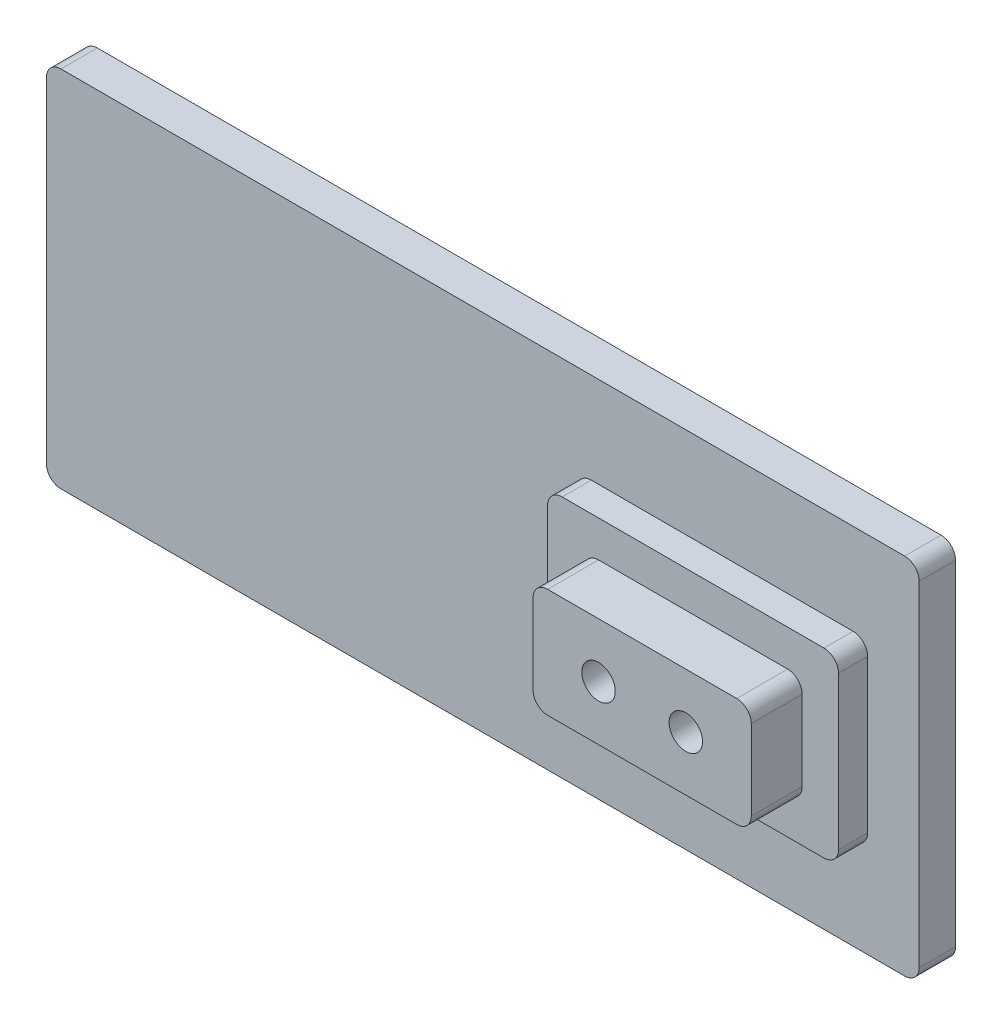
SolidWorks part; units mm, degrees
material "ABS"
ref_plane "Alzado" through (0, 0, 0) normal (0, 0, 1) x (1, 0, 0)
ref_plane "Planta" through (0, 0, 0) normal (0, 1, 0) x (1, 0, 0)
ref_plane "Vista lateral" through (0, 0, 0) normal (1, 0, 0) x (0, 0, -1)
sketch "Croquis1" plane through (0, 0, 0) normal (0, 0, 1) x (1, 0, 0)
  line L0 (-6, 0) -> (6, 0) construction
  line L5 (-15, -7.5) -> (15, -7.5)
  line L6 (-15, -7.5) -> (-15, 7.5)
  line L7 (-15, 7.5) -> (15, 7.5)
  line L8 (15, -7.5) -> (15, 7.5)
  line L9 (-15, -7.5) -> (15, 7.5) construction
  line L10 (-15, 7.5) -> (15, -7.5) construction
  circle A0 centre (6, 0) radius 2.3
  circle A1 centre (-6, 0) radius 2.3
  point P9 (0, 0)
  point P12 (0, 0)
  dimension "D2" = 4.6
  dimension "D1" = 6
  dimension "D3" = 30
  dimension "D4" = 15
extrude "Saliente-Extruir1" add sketch "Croquis1" along normal blind 16
sketch "Croquis2" plane through (0, 0, 0) normal (0, 0, -1) x (-1, 0, 0)
  line L0 (0, 0) -> (0, 25) construction
  line L1 (-27.0901, 25) -> (92.9099, 25)
  line L2 (-27.0901, 25) -> (-27.0901, -25)
  line L3 (0, 0) -> (-27.0901, 0) construction
  line L4 (-27.0901, -25) -> (92.9099, -25)
  line L5 (92.9099, -25) -> (92.9099, 25)
  circle A0 centre (-6, 0) radius 3.5
  circle A1 centre (6, 0) radius 3.5
  dimension "D1" = 120
  dimension "D2" = 50
extrude "Saliente-Extruir2" add sketch "Croquis2" against normal blind 5
sketch "Croquis3" plane through (0, 0, 5) normal (0, 0, 1) x (1, 0, 0)
  line L1 (-20, -12.5) -> (20, -12.5)
  line L2 (-20, -12.5) -> (-20, 12.5)
  line L3 (-20, 12.5) -> (20, 12.5)
  line L4 (20, -12.5) -> (20, 12.5)
  line L5 (-20, -12.5) -> (20, 12.5) construction
  line L6 (-20, 12.5) -> (20, -12.5) construction
  line L7 (-15, -7.5) -> (15, -7.5)
  line L8 (-15, -7.5) -> (-15, 7.5)
  line L9 (-15, 7.5) -> (15, 7.5)
  line L10 (15, -7.5) -> (15, 7.5)
  line L11 (-15, -7.5) -> (15, 7.5) construction
  line L12 (-15, 7.5) -> (15, -7.5) construction
  point P0 (0, 0)
  point P6 (0, 0)
  dimension "D1" = 40
  dimension "D2" = 25
extrude "Saliente-Extruir3" add sketch "Croquis3" along normal blind 4
sketch "Croquis4" plane through (0, 0, 0) normal (0, 0, -1) x (-1, 0, 0)
  line L0 (6, 7.5) -> (-6, 7.5)
  line L1 (6, -7.5) -> (-6, -7.5)
  arc A0 (-6, 7.5) -> (-6, -7.5) centre (-6, 0) ccw
  arc A1 (6, -7.5) -> (6, 7.5) centre (6, 0) ccw
  dimension "D1" = 15
extrude "Cortar-Extruir1" cut sketch "Croquis4" against normal blind 5
fillet "Redondeo1" radius 2 12 edges at (15, -7.5, 12.5) (15, 7.5, 12.5) (-15, 7.5, 12.5) (-15, -7.5, 12.5) (-20, -12.5, 7) (20, -12.5, 7) (20, 12.5, 7) (-20, 12.5, 7) (-92.9099, -25, 2.5) (-92.9099, 25, 2.5) (27.0901, -25, 2.5) (27.0901, 25, 2.5)
